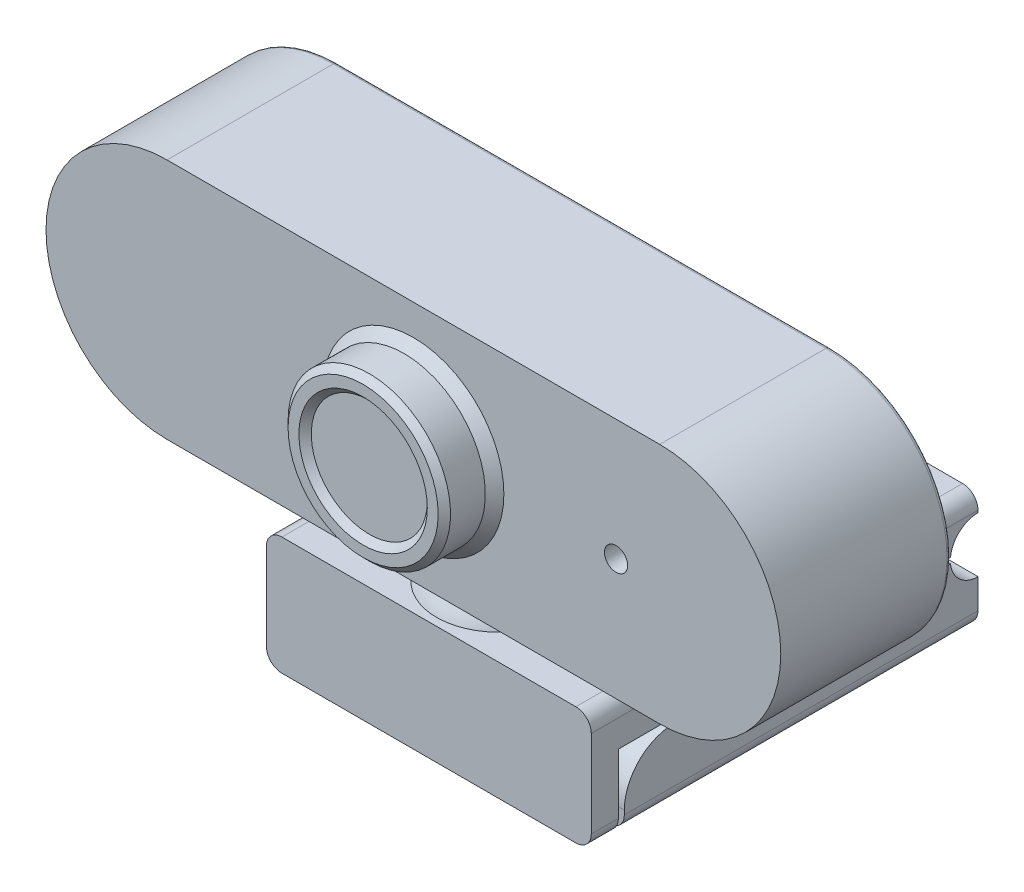
SolidWorks part; units mm, degrees
ref_plane "Plano frontal" through (0, 0, 0) normal (0, 0, 1) x (1, 0, 0)
ref_plane "Plano superior" through (0, 0, 0) normal (0, 1, 0) x (1, 0, 0)
ref_plane "Plano direito" through (0, 0, 0) normal (1, 0, 0) x (0, 0, -1)
sketch "Esboço1" plane through (0, 0, 0) normal (0, 0, 1) x (1, 0, 0)
  line L0 (-31.85, 0) -> (31.85, 0) construction
  line L1 (-31.85, 15.65) -> (31.85, 15.65)
  line L2 (-31.85, -15.65) -> (31.85, -15.65)
  line L3 (0, 0) -> (0, 24.8854) construction
  line L4 (0, 24.8854) -> (-47.5, 24.8854) construction
  line L5 (-47.5, 24.8854) -> (-47.5, -9.4337) construction
  arc A0 (-31.85, 15.65) -> (-31.85, -15.65) centre (-31.85, 0) ccw
  arc A1 (31.85, -15.65) -> (31.85, 15.65) centre (31.85, 0) ccw
  point P3 (0, 0)
  dimension "D1" = 47.5
  dimension "D2" = 31.3
extrude "Ressalto-extrusão1" add sketch "Esboço1" along normal blind 22
sketch "Esboço2" plane through (0, 0, 22) normal (0, 0, 1) x (1, 0, 0)
  circle A0 centre (0, 0) radius 10.5
  circle A1 centre (0, 0) radius 7.5
  dimension "D1" = 21
  dimension "D2" = 3
extrude "Ressalto-extrusão2" add sketch "Esboço2" along normal blind 6.5
chamfer "Chanfro1" distance 0.8 angle 45 2 edges at (7.5, 0, 28.5) (10.5, 0, 28.5)
chamfer "Chanfro2" distance 1.2 angle 45 1 edges at (10.5, 0, 22)
ref_plane "Plano1" through (0, 0, 27.7) normal (0, 0, 1) x (1, 0, 0)
sketch "Esboço3" plane through (0, 0, 27.7) normal (0, 0, 1) x (1, 0, 0)
  circle A0 centre (0, 0) radius 7.5 construction
  circle A1 centre (0, 0) radius 7.5
extrude "Ressalto-extrusão3" add sketch "Esboço3" against normal blind 1
sketch "Esboço4" plane through (0, 0, 22) normal (0, 0, 1) x (1, 0, 0)
  line L0 (11.7, 0) -> (11.7, 9.2038) construction
  circle A0 centre (26.2, 0) radius 1.5
  circle A1 centre (0, 0) radius 11.7 construction
  dimension "D2" = 3
  dimension "D1" = 14.5
extrude "Corte-extrusão1" cut sketch "Esboço4" against normal blind 18
sketch "Esboço5" plane through (0, -15.65, 0) normal (0, -1, 0) x (1, 0, 0)
  line L0 (0, 22) -> (0, 0) construction
  line L3 (-31.85, 22) -> (31.85, 22) construction
  circle A0 centre (0, 11) radius 8
  point P5 (0, 11)
  dimension "D1" = 16
extrude "Ressalto-extrusão4" add sketch "Esboço5" along normal blind 3
fillet "Filete2" radius 0.5 6 edges at (-47.5, 0, 0) (0, 15.65, 0) (47.5, 0, 0) (0, -18.65, 3) (0, -15.65, 19) (0, -15.65, 0)
ref_plane "Plano2" through (0, -21.15, 0) normal (0, -1, 0) x (-1, 0, 0)
sketch "Esboço6" plane through (0, -21.15, 0) normal (0, -1, 0) x (-1, 0, 0)
  line L0 (31.85, -22) -> (-31.85, -22) construction
  line L1 (21, -20) -> (-21, -20)
  line L2 (21, -20) -> (21, 30)
  line L3 (21, 30) -> (-21, 30)
  line L4 (-21, -20) -> (-21, 30)
  line L5 (21, -20) -> (-21, 30) construction
  line L6 (21, 30) -> (-21, -20) construction
  line L7 (0, 0) -> (0, 23.2015) construction
  point P0 (0, 5)
  dimension "D1" = 42
  dimension "D2" = 50
  dimension "D3" = 2
extrude "Ressalto-extrusão5" add sketch "Esboço6" along normal blind 15.25 separate body
fillet "Filete3" radius 2 4 edges at (21, -36.4, -5) (-21, -36.4, -5) (21, -21.15, -5) (-21, -21.15, -5)
sketch "Esboço7" plane through (-21, 0, 0) normal (-1, 0, 0) x (0, 0, 1)
  line L0 (-30, -26.65) -> (16.5, -26.65)
  line L1 (16.5, -26.65) -> (16.5, -38.0467)
  line L2 (-30, -21.15) -> (20, -21.15) construction
  line L3 (20, -34.4) -> (20, -23.15) construction
  line L4 (-30, -26.65) -> (-31.6167, -26.65)
  line L5 (-30, -34.4) -> (-30, -23.15) construction
  line L6 (-30, -27.3624) -> (9.2304, -27.3624)
  line L7 (15.7304, -33.8624) -> (15.7304, -38.0467)
  line L8 (-30, -27.3624) -> (-31.6167, -27.3624)
  line L11 (15.7304, -38.0467) -> (16.5, -38.0467)
  line L12 (-31.6167, -26.65) -> (-31.6167, -27.3624)
  arc A0 (9.2304, -27.3624) -> (15.7304, -33.8624) centre (9.2304, -33.8624) cw
  dimension "D3" = 6.5
  dimension "D1" = 5.5
  dimension "D2" = 3.5
extrude "Corte-extrusão2" cut sketch "Esboço7" against normal blind 70.25 and the other way blind 19
sketch "Esboço8" plane through (0, 0, 0) normal (1, 0, 0) x (0, 0, -1)
  line L0 (30, -26.65) -> (30, -27.3624) construction
  circle A0 centre (30, -27.0062) radius 3.575
  dimension "D1" = 7.15
extrude "Corte-extrusão3" cut sketch "Esboço8" against normal blind 34.25 and the other way blind 36
sketch "Esboço9" plane through (0, 0, 0) normal (1, 0, 0) x (0, 0, -1)
  circle A0 centre (30, -27.0062) radius 3.575
extrude "Ressalto-extrusão6" add sketch "Esboço9" along normal mid plane 21.7
sketch "Esboço10" plane through (0, -36.4, 0) normal (0, -1, 0) x (1, 0, 0)
  line L0 (0, 15.7304) -> (0, -30) construction
  line L1 (19, 15.7304) -> (-19, 15.7304) construction
  line L2 (10.85, -30) -> (-10.85, -30) construction
  circle A0 centre (0, -7.1348) radius 3.5
  dimension "D1" = 7
extrude "Corte-extrusão4" cut sketch "Esboço10" against normal blind 5.7
sketch "Esboço11" plane through (0, -18.65, 0) normal (0, -1, 0) x (1, 0, 0)
  point P0 (0, 11)
ref_plane "Plano3" through (0, 0, 11) normal (0, 0, 1) x (1, 0, 0)
sketch "Esboço12" plane through (0, 0, 11) normal (0, 0, 1) x (1, 0, 0)
  line L0 (-8, -21.15) -> (-8, -18.65) construction
  line L1 (19, -21.15) -> (-19, -21.15) construction
  line L2 (-7.5, -18.65) -> (7.5, -18.65) construction
  line L3 (-8, -18.65) -> (0, -18.65) construction
  line L5 (-8, -16.15) -> (-8, -18.15) construction
  line L7 (0, -15.65) -> (0, -21.15)
  line L8 (0, -21.15) -> (-8, -21.15)
  arc A0 (-8, -21.15) -> (0, -15.65) centre (0, -24.2182) cw
  dimension "D1" = 0
revolve "Revolução1" add sketch "Esboço12" angle 360 about L7
sketch "Esboço13" plane through (0, 0, 0) normal (0, 0, -1) x (-1, 0, 0)
  line L0 (31.85, -15.65) -> (-31.85, -15.65) construction
  circle A0 centre (-26.85, -7.65) radius 2
  arc A1 (-31.85, 15.65) -> (-31.85, -15.65) centre (-31.85, 0) ccw construction
  dimension "D1" = 4
  dimension "D2" = 8
  dimension "D3" = 5
extrude "Ressalto-extrusão7" add sketch "Esboço13" along normal blind 10
sketch "Esboço14" plane through (0, 0, 22) normal (0, 0, 1) x (1, 0, 0)
  point P0 (0, 0)
  point P1 (-55.0368, 12.878)
ref_plane "Plano4" through (0, 0, 0) normal (0, 1, 0) x (1, 0, 0)
sketch "Esboço15" plane through (0, 0, 0) normal (0, 1, 0) x (1, 0, 0)
  line L3 (-150, -172) -> (0, -22) construction
  line L4 (0, -22) -> (150, -172) construction
ref_plane "Plano5" through (0, 0, 0) normal (1, 0, 0) x (0, 0, -1)
sketch "Esboço16" plane through (0, 0, 0) normal (1, 0, 0) x (0, 0, -1)
  line L0 (-22, 0) -> (-172, 150) construction
  line L1 (-22, 15.65) -> (-22, -15.65) construction
  line L2 (-22, 0) -> (-172, -150) construction
  line L3 (-172, 0) -> (-22, 0) construction
  dimension "D1" = 90
  dimension "D2" = 45
